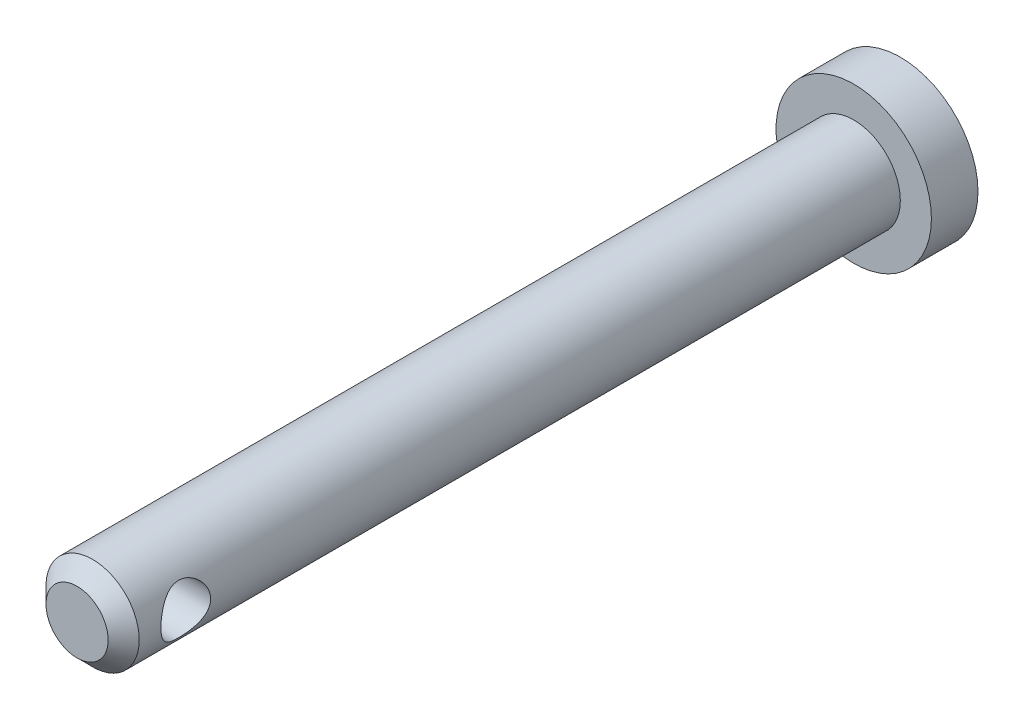
SolidWorks part; units mm, degrees
ref_plane "Front" through (0, 0, 0) normal (0, 0, 1) x (1, 0, 0)
ref_plane "Top" through (0, 0, 0) normal (0, 1, 0) x (1, 0, 0)
ref_plane "Right" through (0, 0, 0) normal (1, 0, 0) x (0, 0, -1)
sketch "草图1" plane through (0, 0, 0) normal (0, 0, 1) x (1, 0, 0)
  circle A0 centre (0, 0) radius 2.5
  dimension "D1" = 5
extrude "凸台-拉伸1" add sketch "草图1" along normal blind 1.5
sketch "草图2" plane through (0, 0, 1.5) normal (0, 0, 1) x (1, 0, 0)
  circle A0 centre (0, 0) radius 1.5
  dimension "D1" = 3
extrude "凸台-拉伸2" add sketch "草图2" along normal blind 25
ref_plane "基准面1" through (1.5, 0, 0) normal (1, 0, 0) x (0, 0, -1)
sketch "草图3" plane through (1.5, 0, 0) normal (1, 0, 0) x (0, 0, -1)
  line L0 (-26.5, 1.5) -> (-26.5, -1.5) construction
  circle A0 centre (-24.5, 0) radius 0.8
  dimension "D1" = 1.6
  dimension "D2" = 2
extrude "切除-拉伸1" cut sketch "草图3" against normal through all
chamfer "倒角1" distance 0.5 angle 45 1 edges at (1.5, 0, 26.5)
